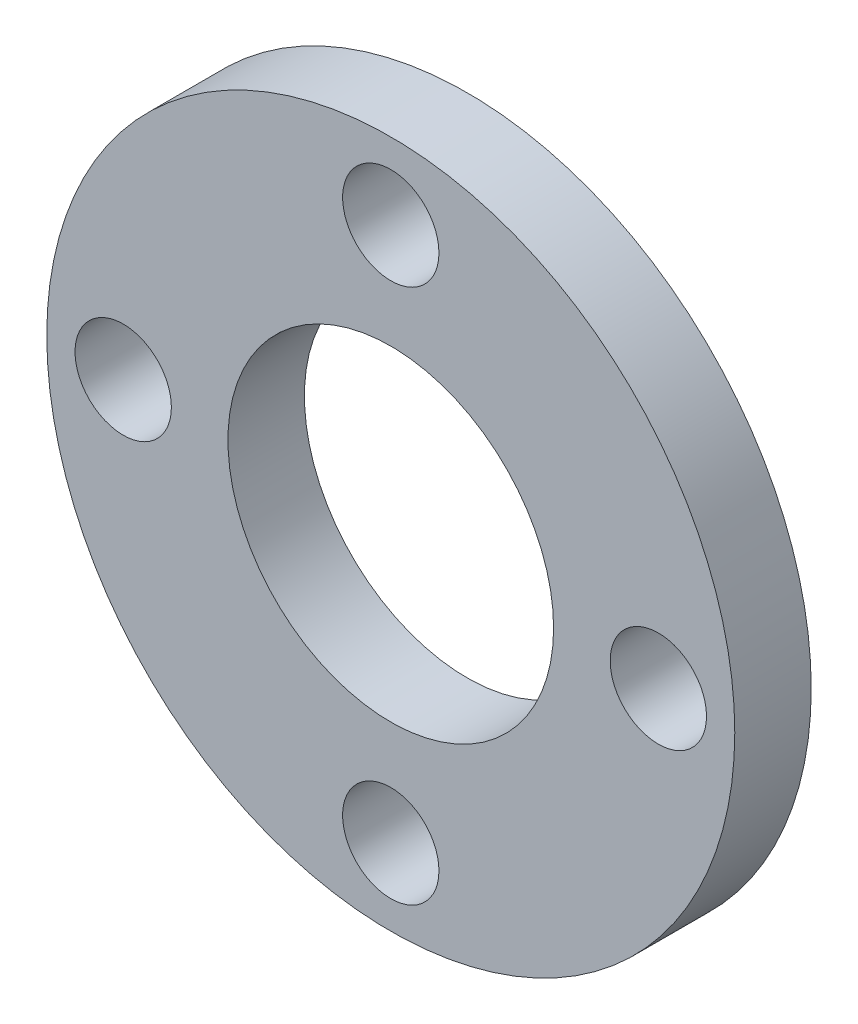
SolidWorks part; units mm, degrees
ref_plane "Płaszczyzna przednia" through (0, 0, 0) normal (0, 0, 1) x (1, 0, 0)
ref_plane "Płaszczyzna górna" through (0, 0, 0) normal (0, 1, 0) x (1, 0, 0)
ref_plane "Płaszczyzna prawa" through (0, 0, 0) normal (1, 0, 0) x (0, 0, -1)
sketch "Szkic1" plane through (0, 0, 0) normal (0, 0, 1) x (1, 0, 0)
  circle A0 centre (0, 0) radius 45
  circle A1 centre (0, 0) radius 35 construction
  circle A2 centre (0, 35) radius 6.3
  circle A3 centre (35, 0) radius 6.3
  circle A4 centre (0, -35) radius 6.3
  circle A5 centre (-35, 0) radius 6.3
  circle A6 centre (0, 0) radius 21.3
  dimension "D1" = 90
  dimension "D2" = 70
  dimension "D3" = 12.6
  dimension "D6" = 42.6
extrude "Dodanie-wyciągnięcie3" add sketch "Szkic1" along normal blind 10 contours A0 A5 A1 A2 A3 A4 | A5 A1 A4 A3 A2 A6
